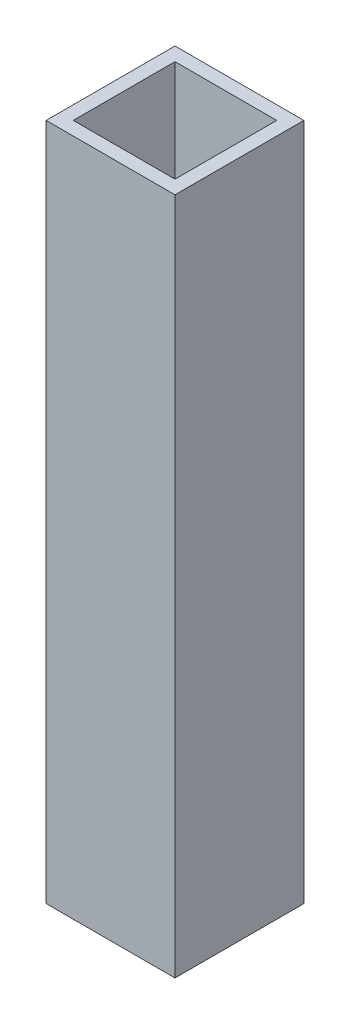
SolidWorks part; units mm, degrees
ref_plane "Front Plane" through (0, 0, 0) normal (0, 0, 1) x (1, 0, 0)
ref_plane "Top Plane" through (0, 0, 0) normal (0, 1, 0) x (1, 0, 0)
ref_plane "Right Plane" through (0, 0, 0) normal (1, 0, 0) x (0, 0, -1)
sketch "Sketch1" plane through (0, 0, 0) normal (0, 1, 0) x (1, 0, 0)
  line L1 (-9.5, -9.5) -> (9.5, -9.5)
  line L2 (-9.5, -9.5) -> (-9.5, 9.5)
  line L3 (-9.5, 9.5) -> (9.5, 9.5)
  line L4 (9.5, -9.5) -> (9.5, 9.5)
  line L5 (-9.5, -9.5) -> (9.5, 9.5) construction
  line L6 (-9.5, 9.5) -> (9.5, -9.5) construction
  point P0 (0, 0)
  dimension "D1" = 19
  dimension "D2" = 19
extrude "Extrude-Thin1" add sketch "Sketch1" along normal blind 100 thin thin type one direction reverse wall 2
